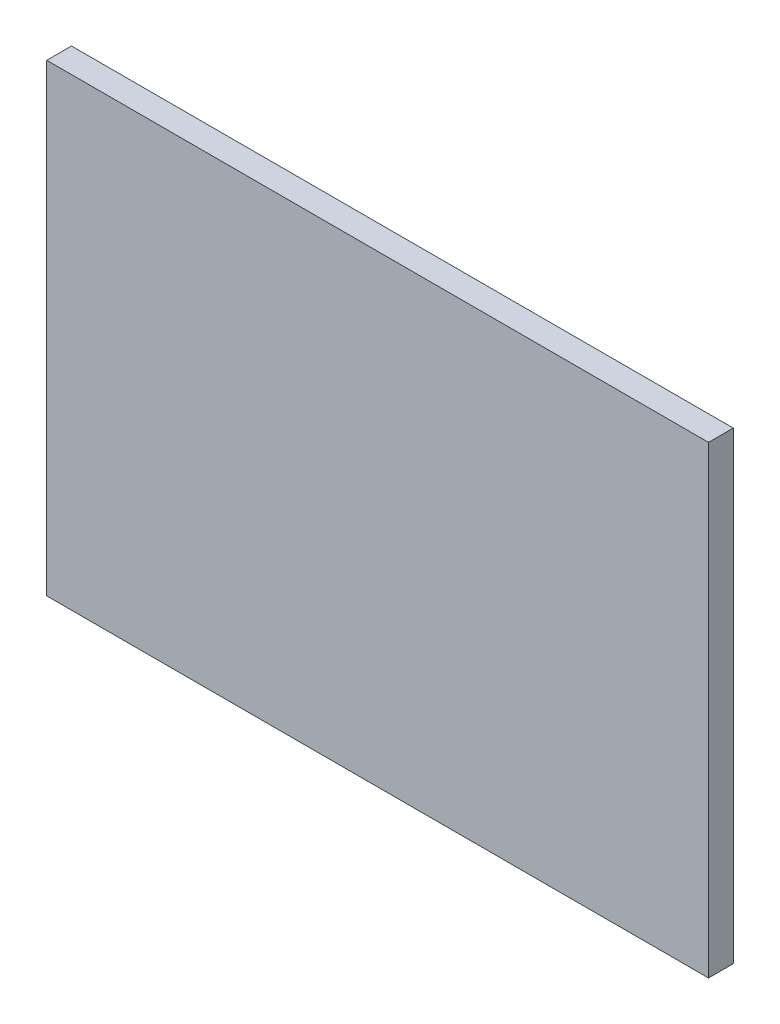
SolidWorks part; units mm, degrees
ref_plane "Спереди" through (0, 0, 0) normal (0, 0, 1) x (1, 0, 0)
ref_plane "Сверху" through (0, 0, 0) normal (0, 1, 0) x (1, 0, 0)
ref_plane "Справа" through (0, 0, 0) normal (1, 0, 0) x (0, 0, -1)
sketch "Эскиз1" plane through (0, 0, 0) normal (0, 0, 1) x (1, 0, 0)
  line L1 (-1605, -1125) -> (1605, -1125)
  line L2 (-1605, -1125) -> (-1605, 1125)
  line L3 (-1605, 1125) -> (1605, 1125)
  line L4 (1605, -1125) -> (1605, 1125)
  line L5 (-1605, -1125) -> (1605, 1125) construction
  line L6 (-1605, 1125) -> (1605, -1125) construction
  point P0 (0, 0)
  dimension "D1" = 2250
  dimension "D2" = 3210
extrude "Бобышка-Вытянуть1" add sketch "Эскиз1" along normal mid plane 120
